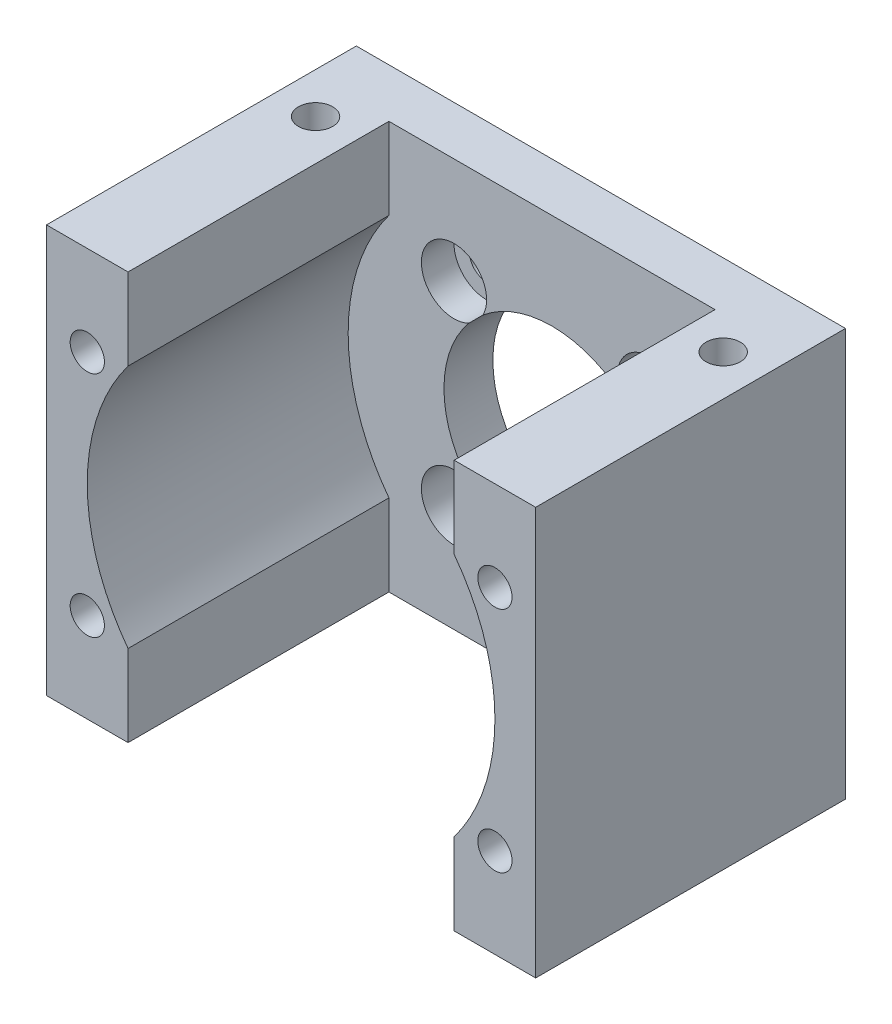
SolidWorks part; units mm, degrees
ref_plane "前视基准面" through (0, 0, 0) normal (0, 0, 1) x (1, 0, 0)
ref_plane "上视基准面" through (0, 0, 0) normal (0, 1, 0) x (1, 0, 0)
ref_plane "右视基准面" through (0, 0, 0) normal (1, 0, 0) x (0, 0, -1)
sketch "草图1" plane through (0, 0, 0) normal (0, 0, 1) x (1, 0, 0)
  line L1 (-30, 25) -> (30, 25)
  line L2 (-30, 25) -> (-30, -25)
  line L3 (-30, -25) -> (30, -25)
  line L4 (30, 25) -> (30, -25)
  line L5 (-30, 25) -> (30, -25) construction
  line L6 (-30, -25) -> (30, 25) construction
  point P0 (0, 0)
  dimension "D1" = 50
  dimension "D2" = 60
extrude "凸台-拉伸1" add sketch "草图1" along normal blind 38
ref_plane "基准面1" through (0, 0, 0) normal (-1, 0, 0) x (0, 0, 1)
ref_plane "基准面2" through (0, 0, 0) normal (0, 1, 0) x (1, 0, 0)
sketch "草图2" plane through (0, 25, 0) normal (0, 1, 0) x (1, 0, 0)
  line L0 (0, 20.9) -> (0, -20.9) construction
  line L1 (-20, -6) -> (20, -6)
  line L2 (-20, -6) -> (-20, -73.4563)
  line L3 (-20, -73.4563) -> (20, -73.4563)
  line L4 (20, -6) -> (20, -73.4563)
  line L5 (-20, -6) -> (20, -73.4563) construction
  line L6 (-20, -73.4563) -> (20, -6) construction
  line L7 (30, 0) -> (-30, 0) construction
  point P0 (0, -39.7281)
  dimension "D1" = 40
  dimension "D2" = 6
extrude "切除-拉伸1" cut sketch "草图2" against normal through all
sketch "草图3" plane through (0, 0, 38) normal (0, 0, 1) x (1, 0, 0)
  circle A0 centre (0, 0) radius 25
  dimension "D1" = 50
extrude "切除-拉伸2" cut sketch "草图3" against normal up to surface (32 mm away) up to face at (0, 0, 6)
sketch "草图4" plane through (0, 0, 0) normal (0, 0, -1) x (-1, 0, 0)
  circle A0 centre (0, 0) radius 13.25
  dimension "D1" = 26.5
extrude "切除-拉伸3" cut sketch "草图4" against normal blind 10
hole_wizard "Ø4.2 (4.2) 直径孔1" positions "草图6" profile "草图5" hole size "Ø4.2" standard "GB" end condition through all
sketch "草图6" plane through (0, 0, 6) normal (0, 0, 1) x (1, 0, 0)
  point P0 (12.0208, 12.0208)
  point P3 (-12.0208, 12.0208)
  point P6 (-12.0208, -12.0208)
  point P9 (12.0208, -12.0208)
sketch "草图5" plane through (12.0208, 12.0208, 6) normal (1, 0, 0) x (0, -1, 0)
  line L0 (0, 0) -> (0, 6)
  line L1 (0, 6) -> (2.1, 6)
  line L2 (2.1, 6) -> (2.1, 0)
  line L5 (2.1, 0) -> (0, 0)
  line L11 (0, -6.35) -> (0, 107.95) construction
  dimension "通孔孔直径" = 4.2
  dimension "通孔孔深度" = 6
hole_wizard "M5 螺纹孔1" positions "草图8" profile "草图7" tap size "M5" standard "GB"
sketch "草图8" plane through (0, 0, 38) normal (0, 0, 1) x (1, 0, 0)
  line L0 (20.9, 0) -> (-20.9, 0) construction
  line L1 (0, 20.9) -> (0, -20.9) construction
  point P0 (25, 14)
  dimension "D1" = 14
  dimension "D2" = 25
sketch "草图7" plane through (25, 14, 38) normal (1, 0, 0) x (0, -1, 0)
  line L0 (0, 0) -> (0, 23.6618)
  line L1 (0, 23.6618) -> (2.1, 22.4)
  line L2 (2.1, 22.4) -> (2.1, 0)
  line L5 (2.1, 0) -> (0, 0)
  line L10 (0, 23.6618) -> (-2.1, 22.4) construction
  line L11 (0, -6.35) -> (0, 107.95) construction
  dimension "螺纹孔钻头直径" = 4.2
  dimension "螺纹孔钻头深度" = 22.4
  dimension "导头角度" = 118
cosmetic thread "孔螺蚊线1" parameters "D1"=20, "D2"=5
mirror "镜向1" about plane through (0, 0, 0) normal (0, 1, 0) of "M5 螺纹孔1"
mirror "镜向2" about plane through (0, 0, 0) normal (-1, 0, 0) of "镜向1", "M5 螺纹孔1"
hole_wizard "M5 螺纹孔2" positions "草图10" profile "草图9" tap size "M5" standard "GB"
sketch "草图10" plane through (0, 25, 0) normal (0, 1, 0) x (1, 0, 0)
  line L0 (30, 0) -> (-30, 0) construction
  line L1 (0, 20.9) -> (0, -20.9) construction
  point P0 (-25, -10)
  point P2 (25, -10)
  dimension "D1" = 10
  dimension "D2" = 10
  dimension "D3" = 25
  dimension "D4" = 25
sketch "草图9" plane through (-25, 25, 10) normal (1, 0, 0) x (0, 0, 1)
  line L0 (0, 0) -> (0, 13.6618)
  line L1 (0, 13.6618) -> (2.1, 12.4)
  line L2 (2.1, 12.4) -> (2.1, 0)
  line L5 (2.1, 0) -> (0, 0)
  line L10 (0, 13.6618) -> (-2.1, 12.4) construction
  line L11 (0, -6.35) -> (0, 107.95) construction
  dimension "螺纹孔钻头直径" = 4.2
  dimension "螺纹孔钻头深度" = 12.4
  dimension "导头角度" = 118
cosmetic thread "孔螺蚊线2" parameters "D1"=10, "D2"=5
cosmetic thread "孔螺蚊线3" parameters "D1"=10, "D2"=5
mirror "镜向3" about plane through (0, 0, 0) normal (0, 1, 0) of "M5 螺纹孔2"
sketch "草图11" plane through (0, 0, 6) normal (0, 0, 1) x (1, 0, 0)
  circle A0 centre (12.0208, 12.0208) radius 4
  dimension "D1" = 8
extrude "切除-拉伸4" cut sketch "草图11" against normal blind 4
pattern_circular "阵列(圆周)1" count 4 every 90 about axis through (0, 0, 0) along (0, 0, 1) of "切除-拉伸4"
